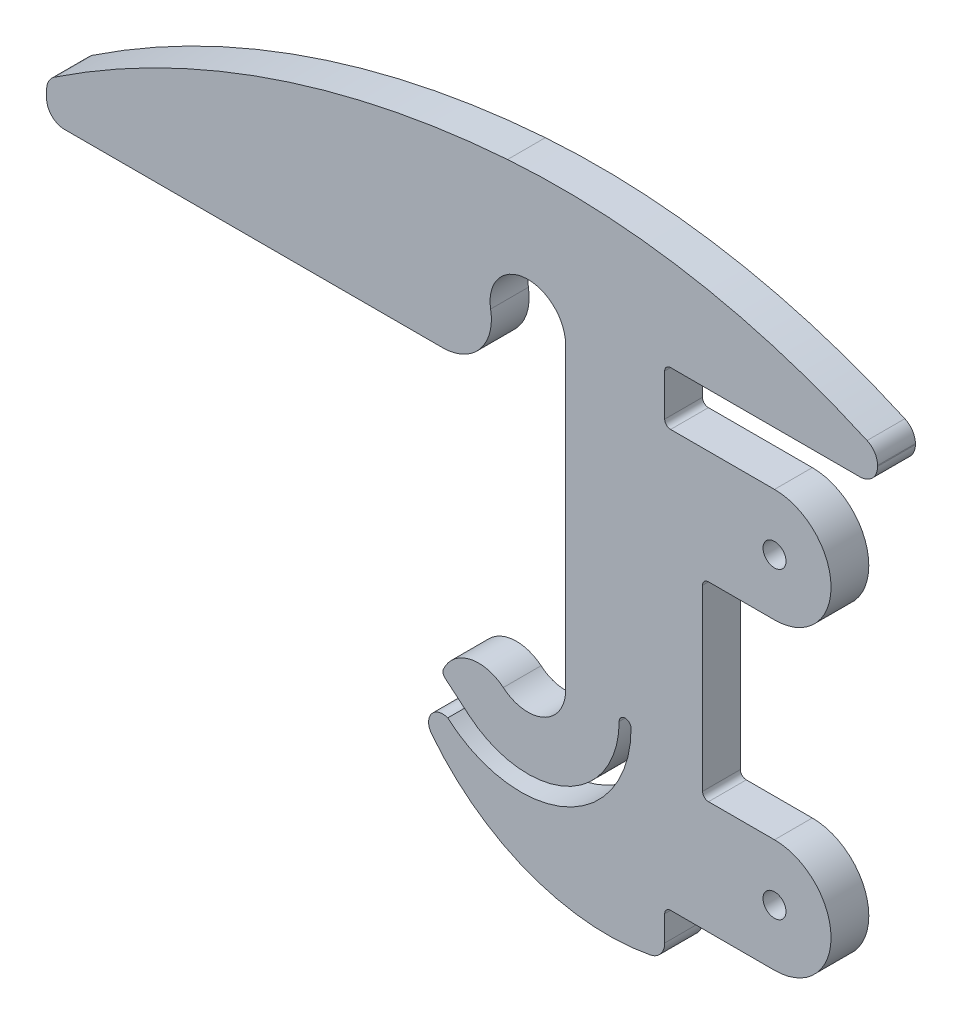
SolidWorks part; units mm, degrees
ref_plane "Front Plane" through (0, 0, 0) normal (0, 0, 1) x (1, 0, 0)
ref_plane "Top Plane" through (0, 0, 0) normal (0, 1, 0) x (1, 0, 0)
ref_plane "Right Plane" through (0, 0, 0) normal (1, 0, 0) x (0, 0, -1)
sketch "Model" plane through (0, 0, 0) normal (0, 0, 1) x (1, 0, 0)
  line L1 (14.6829, 1.325) -> (14.6829, -14.675)
  line L2 (29.3928, 17.8652) -> (29.3928, 15.325)
  line L3 (29.3928, 15.325) -> (11.5, 15.325)
  line L4 (11.5, 10.825) -> (11.5, 15.325)
  line L5 (20.7299, 10.825) -> (11.5, 10.825)
  line L6 (20.7299, 1.325) -> (14.6829, 1.325)
  line L7 (29.5, -24.175) -> (12, -24.175) construction
  line L8 (12, -14.675) -> (29.4597, -14.675) construction
  line L9 (20.7299, -24.175) -> (11.5, -24.175)
  line L11 (15.1829, -14.2727) -> (15.1829, 0.9673) construction
  line L13 (12, 14.825) -> (29.4597, 14.825) construction
  line L14 (14.6829, -14.675) -> (20.7299, -14.675)
  line L15 (11.5, -24.175) -> (11.5, -28.0042)
  line L16 (29.5, 10.825) -> (12, 10.825) construction
  line L17 (12, -24.175) -> (12, -28.175) construction
  line L30 (-40.4406, 9.3328) -> (-40.4406, 8.6908)
  line L31 (-38.9406, 7.1908) -> (-7.182, 7.1908)
  line L32 (3.175, 12.575) -> (3.175, -12.575)
  line L33 (-7.2315, -16.526) -> (-4.9334, -18.4544)
  arc A0 (-1.7042, 23.6193) -> (29.3928, 17.8652) centre (2.8223, -38.8245) cw
  arc A1 (20.7299, 10.825) -> (20.7299, 1.325) centre (20.7299, 6.075) cw
  arc A2 (20.7299, -14.675) -> (20.7299, -24.175) centre (20.7299, -19.425) cw
  arc A3 (-8.0912, -21.3717) -> (11.5, -28.0042) centre (6.7381, -9.8191) ccw
  arc A4 (3.175, -12.575) -> (-2.0615, -14.9897) centre (0, -12.575) cw
  arc A5 (-4.9334, -18.4544) -> (7.675, -12.5941) centre (0, -12.575) ccw
  arc A6 (7.675, -12.5941) -> (8.675, -12.5954) centre (8.175, -12.5954) cw
  arc A7 (8.675, -12.5954) -> (-6.7315, -19.5356) centre (-0.5917, -12.5948) cw
  arc A8 (-8.0912, -21.3717) -> (-6.7315, -19.5356) centre (-7.1557, -20.643) cw
  arc A21 (-1.7042, 23.6193) -> (-39.7721, 10.5812) centre (4.0052, -55.1441) ccw
  arc A22 (-39.7721, 10.5812) -> (-40.4406, 9.3328) centre (-38.9406, 9.3328) ccw
  arc A23 (-40.4406, 8.6908) -> (-38.9406, 7.1908) centre (-38.9406, 8.6908) ccw
  arc A24 (-7.182, 7.1908) -> (-3.1268, 12.0237) centre (-7.182, 11.3086) ccw
  arc A25 (3.175, 12.575) -> (-3.1268, 12.0237) centre (0, 12.575) ccw
  arc A27 (-2.0615, -14.9897) -> (-7.2315, -16.526) centre (-4.1298, -17.4966) ccw
  dimension "D1" = 11.5
  dimension "D6" = 0.5
  dimension "D2" = 0.5
  dimension "D3" = 0.5
  dimension "D4" = 0
  dimension "D5" = 0.5
extrude "Boss-Extrude1" add sketch "Model" along normal blind 3.175
fillet "Fillet1" radius 0.5 6 edges at (-7.2315, -16.526, 1.5875) (11.5, -24.175, 1.5875) (14.6829, -14.675, 1.5875) (14.6829, 1.325, 1.5875) (11.5, 10.825, 1.5875) (11.5, 15.325, 1.5875)
sketch "Sketch3" plane through (0, 0, 0) normal (0, 0, -1) x (-1, 0, 0)
  circle A0 centre (-20.7299, 6.075) radius 0.9652
  circle A1 centre (-20.7299, -19.425) radius 0.9652
extrude "Cut-Extrude2" cut sketch "Sketch3" against normal up to next
fillet "Fillet2" radius 1.5 3 edges at (11.5, -28.0042, 1.5875) (29.3928, 15.325, 1.5875) (29.3928, 17.8652, 1.5875)
